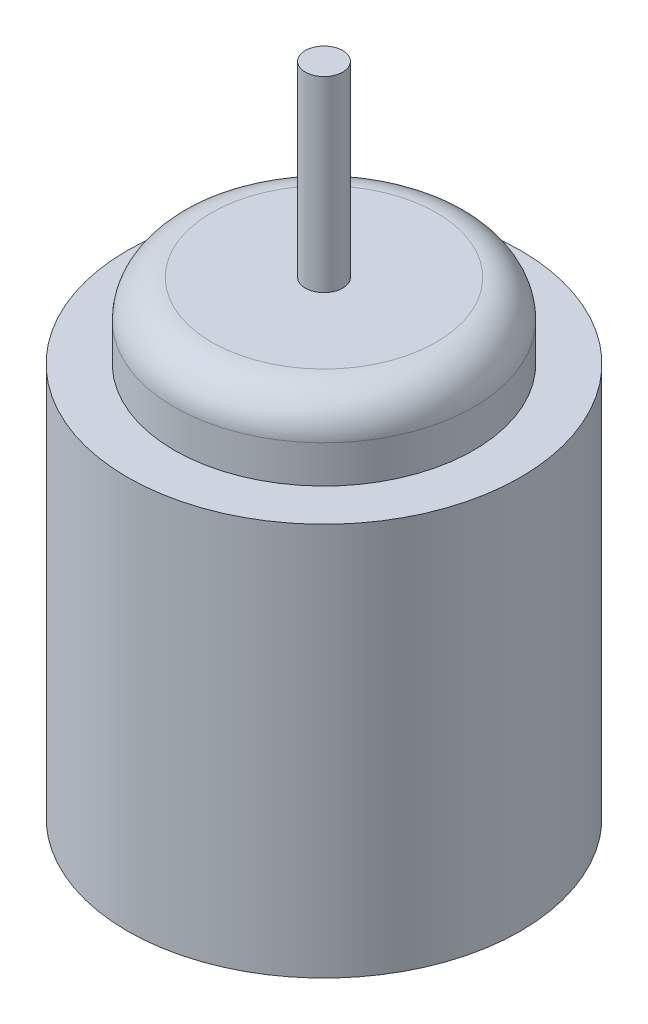
SolidWorks part; units mm, degrees
ref_plane "前基準面" through (0, 0, 0) normal (0, 0, 1) x (1, 0, 0)
ref_plane "上基準面" through (0, 0, 0) normal (0, 1, 0) x (1, 0, 0)
ref_plane "右基準面" through (0, 0, 0) normal (1, 0, 0) x (0, 0, -1)
sketch "草圖1" plane through (0, 0, 0) normal (0, 1, 0) x (1, 0, 0)
  circle A0 centre (0, 0) radius 10.5
  dimension "D1" = 21
extrude "填料-伸長1" add sketch "草圖1" along normal blind 21
sketch "草圖2" plane through (0, 21, 0) normal (0, 1, 0) x (1, 0, 0)
  circle A0 centre (0, 0) radius 8
  dimension "D1" = 16
extrude "填料-伸長2" add sketch "草圖2" along normal blind 4
fillet "圓角1" radius 2 1 edges at (0, 25, 8)
sketch "草圖3" plane through (0, 25, 0) normal (0, 1, 0) x (1, 0, 0)
  circle A0 centre (0, 0) radius 1
  dimension "D1" = 2
extrude "填料-伸長3" add sketch "草圖3" along normal blind 10
